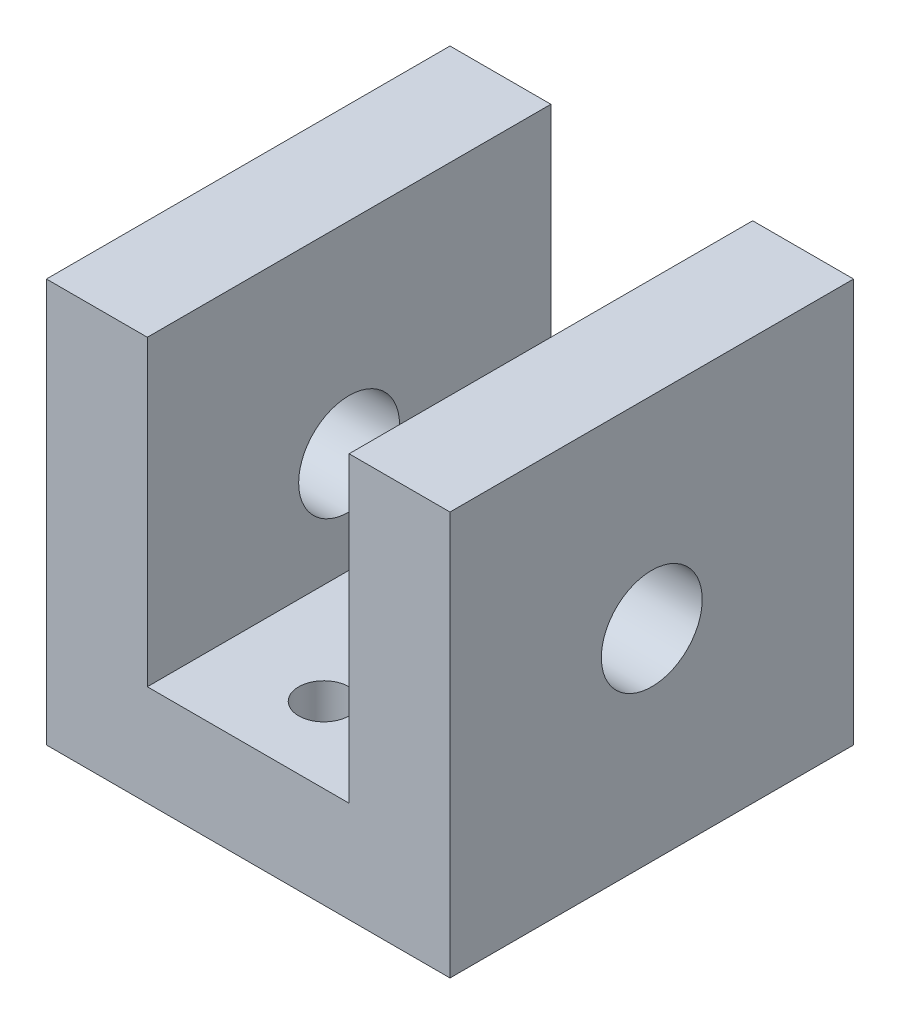
SolidWorks part; units mm, degrees
material "6061 Alloy"
ref_plane "Front Plane" through (0, 0, 0) normal (0, 0, 1) x (1, 0, 0)
ref_plane "Top Plane" through (0, 0, 0) normal (0, 1, 0) x (1, 0, 0)
ref_plane "Right Plane" through (0, 0, 0) normal (1, 0, 0) x (0, 0, -1)
sketch "Sketch1" plane through (0, 0, 0) normal (0, 0, 1) x (1, 0, 0)
  line L0 (0, 0) -> (0, 50.8)
  line L1 (0, 50.8) -> (12.7, 50.8)
  line L2 (12.7, 50.8) -> (12.7, 12.7)
  line L3 (12.7, 12.7) -> (38.1, 12.7)
  line L4 (38.1, 12.7) -> (38.1, 50.8)
  line L5 (38.1, 50.8) -> (50.8, 50.8)
  line L6 (50.8, 50.8) -> (50.8, 0)
  line L7 (50.8, 0) -> (0, 0)
  dimension "D1" = 12.7
  dimension "D2" = 12.7
  dimension "D3" = 12.7
  dimension "D4" = 50.8
  dimension "D5" = 50.8
extrude "Extrude1" add sketch "Sketch1" along normal blind 50.8
sketch "Sketch2" plane through (0, 0, 0) normal (0, -1, 0) x (1, 0, 0)
  line L0 (50.8, 50.8) -> (50.8, 0) construction
  line L1 (0, 50.8) -> (50.8, 50.8) construction
  circle A0 centre (25.4, 41.275) radius 3.175
  circle A1 centre (25.4, 9.525) radius 3.175
  dimension "D4" = 6.35
  dimension "D5" = 6.35
  dimension "D1" = 31.75
  dimension "D2" = 25.4
  dimension "D3" = 9.525
extrude "Cut-Extrude1" cut sketch "Sketch2" against normal through all
sketch "Sketch3" plane through (50.8, 0, 0) normal (1, 0, 0) x (0, 0, -1)
  line L0 (-50.8, 0) -> (0, 0) construction
  line L2 (0, 0) -> (0, 50.8) construction
  circle A0 centre (-25.4, 25.4) radius 6.35
  dimension "D1" = 12.7
  dimension "D2" = 25.4
  dimension "D3" = 25.4
extrude "Cut-Extrude2" cut sketch "Sketch3" against normal through all
